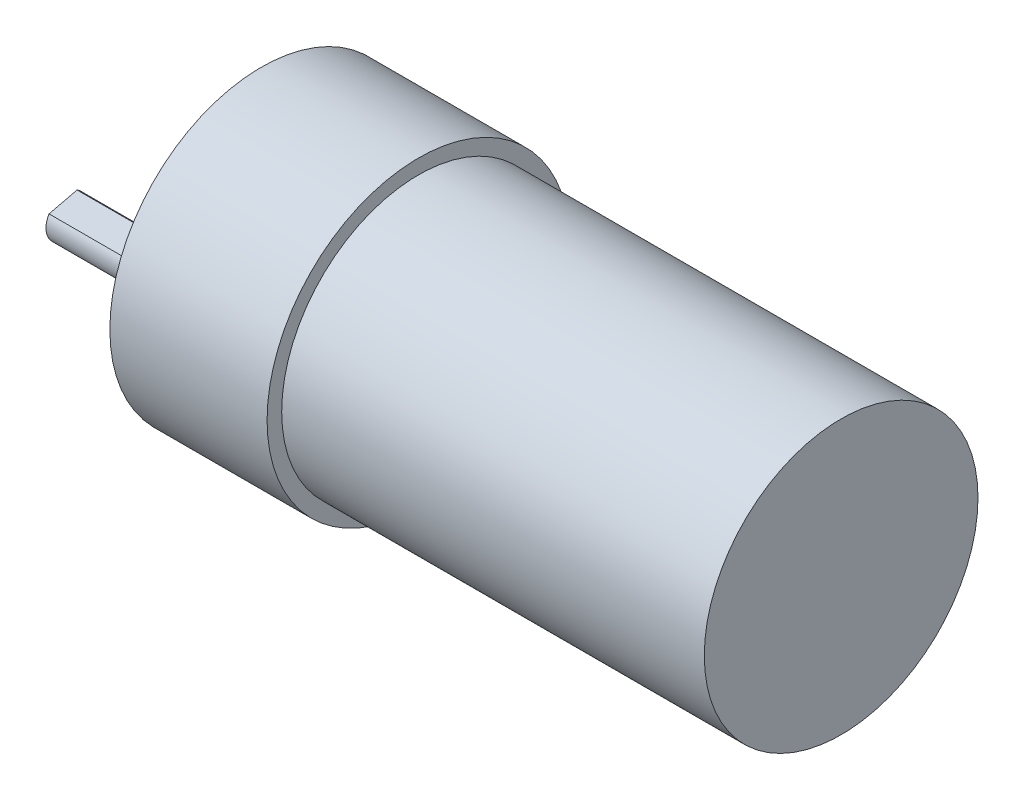
SolidWorks part; units mm, degrees
material "Steel Shell"
ref_plane "Front Plane" through (0, 0, 0) normal (0, 0, 1) x (1, 0, 0)
ref_plane "Top Plane" through (0, 0, 0) normal (0, 1, 0) x (1, 0, 0)
ref_plane "Right Plane" through (0, 0, 0) normal (1, 0, 0) x (0, 0, -1)
sketch "Sketch1" plane through (0, 0, 0) normal (1, 0, 0) x (0, 0, -1)
  circle A0 centre (0, 0) radius 15.875
  dimension "D1" = 31.75
extrude "Extrude1" add sketch "Sketch1" along normal blind 49.022
sketch "Sketch3" plane through (0, 0, 0) normal (-1, 0, 0) x (0, 0, 1)
  circle A0 centre (0, 0) radius 17.5692
extrude "Extrude3" add sketch "Sketch3" along normal blind 18.2372
sketch "Sketch4" plane through (-18.2372, 0, 0) normal (-1, 0, 0) x (0, 0, 1)
  line L0 (0, 0) -> (0, -8.7186) construction
  circle A0 centre (0, -8.7186) radius 2.3749
  dimension "D2" = 4.7498
  dimension "D1" = 8.7186
extrude "Extrude4" add sketch "Sketch4" along normal blind 22.606
sketch "Sketch5" plane through (-18.2372, 0, 0) normal (-1, 0, 0) x (0, 0, 1)
  line L0 (0, 17.5692) -> (0, 13.4556) construction
  circle A0 centre (0, 0) radius 17.5692 construction
  circle A1 centre (0, 13.4556) radius 1.27
  circle A3 centre (0, -8.7186) radius 2.3749 construction
  dimension "D2" = 2.54
  dimension "D1" = 22.1742
extrude "Cut-Extrude1" cut sketch "Sketch5" against normal blind 10
sketch "Sketch6" plane through (-18.2372, 0, 0) normal (-1, 0, 0) x (0, 0, 1)
  line L0 (0, -8.7186) -> (10.2108, -8.7186) construction
  line L1 (0, -8.7186) -> (-10.2108, -8.7186) construction
  circle A0 centre (10.2108, -8.7186) radius 1.27
  circle A4 centre (0, 13.4556) radius 1.27 construction
  circle A5 centre (-10.2108, -8.7186) radius 1.27
  circle A6 centre (0, 13.4556) radius 1.27 construction
  dimension "D1" = 10.2108
extrude "Cut-Extrude2" cut sketch "Sketch6" against normal blind 10
sketch3d "3DSketch3"
  circle A0 centre (-18.2372, -8.7186, 10.2108) radius 1.27 construction
  point P2 (-19.5072, -8.7186, 10.2108)
sketch "Sketch7" plane through (0, -5.9371, -1.4198) normal (0, 0.9726, 0.2326) x (-1, 0, 0)
  line L0 (25.8572, 1.8493) -> (18.2372, 1.8493) construction
  line L1 (25.8572, 6.9456) -> (43.5843, 6.9456)
  line L2 (25.8572, 6.9456) -> (25.8572, -4.0683)
  line L3 (25.8572, -4.0683) -> (43.5843, -4.0683)
  line L4 (43.5843, 6.9456) -> (43.5843, -4.0683)
  line L5 (18.2372, -0.3471) -> (18.2372, 4.4027) construction
  dimension "D1" = 7.62
extrude "Cut-Extrude3" cut sketch "Sketch7" against normal blind 0.6858
sketch "Sketch9" plane through (0, 0, 0) normal (1, 0, 0) x (0, 0, -1)
  line L0 (0, 0) -> (0, 15.875)
  circle A0 centre (0, 0) radius 15.875 construction
ref_plane "Plane3" through (0, 15.875, 0) normal (0, 1, 0) x (-1, 0, 0)
sketch "Sketch10" [suppressed] plane through (-18.2372, 0, 0) normal (-1, 0, 0) x (0, 0, 1)
  circle A1 centre (0, 13.4556) radius 1.27
  circle A2 centre (0, 13.4556) radius 1.27
  circle A3 centre (0, -8.7186) radius 2.3749
  circle A4 centre (0, -8.7186) radius 2.3749
  circle A5 centre (-10.2108, -8.7186) radius 1.27
  circle A6 centre (-10.2108, -8.7186) radius 1.27
  circle A7 centre (10.2108, -8.7186) radius 1.27
  circle A8 centre (10.2108, -8.7186) radius 1.27
  circle A10 centre (0, 0) radius 17.5692 construction
  circle A11 centre (0, 0) radius 17.5692
  dimension "D1" = 0
  dimension "D2" = 0
  dimension "D3" = 0
  dimension "D4" = 0
